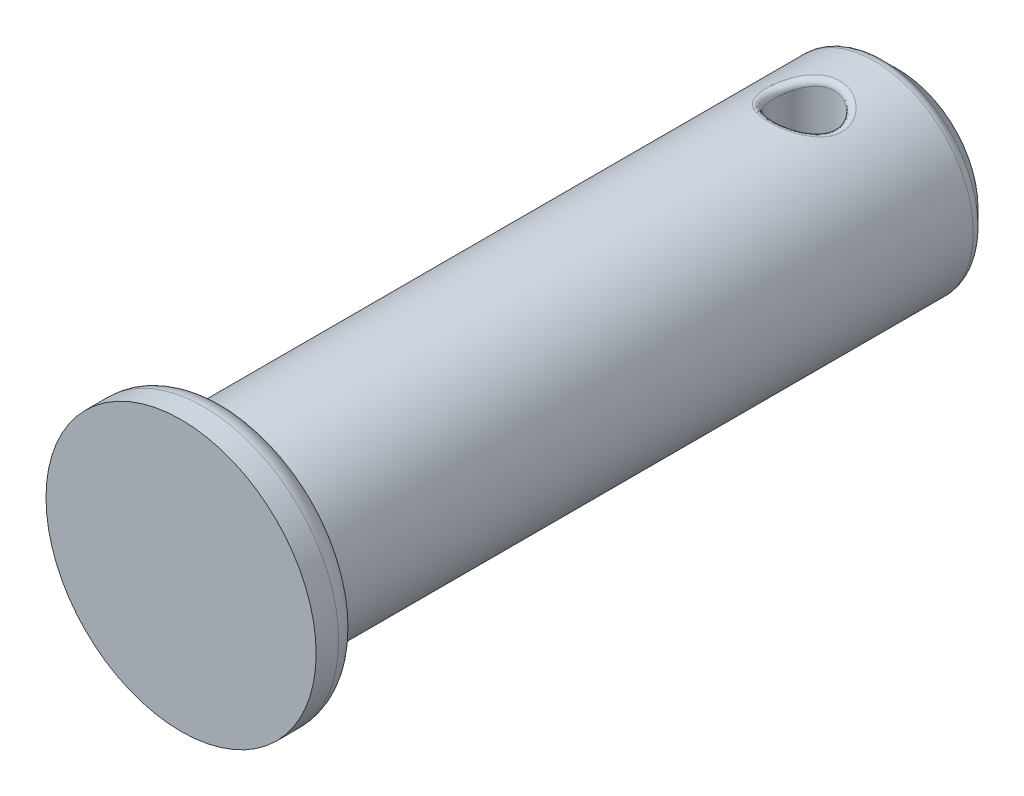
SolidWorks part; units mm, degrees
ref_plane "Front Plane" through (0, 0, 0) normal (0, 0, 1) x (1, 0, 0)
ref_plane "Top Plane" through (0, 0, 0) normal (0, 1, 0) x (1, 0, 0)
ref_plane "Right Plane" through (0, 0, 0) normal (1, 0, 0) x (0, 0, -1)
sketch "Sketch1" plane through (0, 0, 0) normal (0, 0, 1) x (1, 0, 0)
  circle A0 centre (0, 0) radius 3.4925
  dimension "D1" = 6.985
extrude "Boss-Extrude1" add sketch "Sketch1" along normal blind 23.8125
sketch "Sketch2" plane through (0, 0, 23.8125) normal (0, 0, 1) x (1, 0, 0)
  circle A2 centre (0, 0) radius 4.7625
  circle A3 centre (0, 0) radius 4.7625
  dimension "D1" = 1.27
extrude "Boss-Extrude2" add sketch "Sketch2" along normal blind 1.5875
sketch "Sketch3" plane through (0, 0, 0) normal (0, 1, 0) x (1, 0, 0)
  circle A0 centre (0, -3.429) radius 1.0583
  dimension "D1" = 2.1167
  dimension "D2" = 3.429
extrude "Cut-Extrude1" cut sketch "Sketch3" against normal through all both and the other way through all
fillet "Fillet1" radius 0.1984 2 edges at (-0.1905, -3.4873, 2.388) (0.1905, 3.4873, 2.388)
fillet "Fillet3" radius 0.7937 1 edges at (4.7625, 0, 23.8125)
chamfer "Chamfer1" distance 0.7937 angle 45 1 edges at (3.4925, 0, 0)
fillet "Fillet4" radius 0.3969 2 edges at (2.6987, 0, 0) (3.4925, 0, 0.7937)
